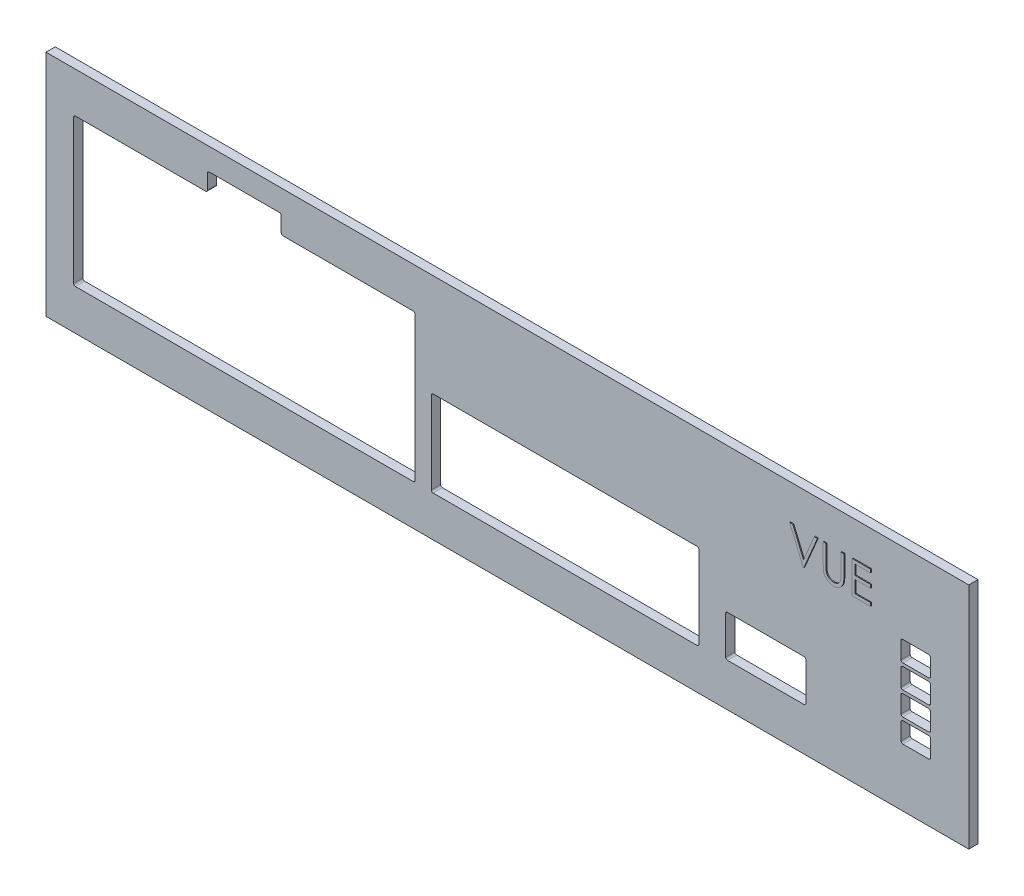
SolidWorks part; units mm, degrees
material "6061-T6 (SS)"
ref_plane "Plan de face" through (0, 0, 0) normal (0, 0, 1) x (1, 0, 0)
ref_plane "Plan de dessus" through (0, 0, 0) normal (0, 1, 0) x (1, 0, 0)
ref_plane "Plan de droite" through (0, 0, 0) normal (1, 0, 0) x (0, 0, -1)
sketch "Esquisse1" plane through (0, 0, 0) normal (0, 0, 1) x (1, 0, 0)
  line L1 (-50, 12.4) -> (50, 12.4)
  line L2 (-50, 12.4) -> (-50, -12.4)
  line L3 (-50, -12.4) -> (50, -12.4)
  line L4 (50, 12.4) -> (50, -12.4)
  point P4 (0, 12.4)
  point P7 (-50, 0)
  dimension "D1" = 100
  dimension "D2" = 24.8
extrude "Boss.-Extru.1" add sketch "Esquisse1" along normal blind 1
sketch "Esquisse2" plane through (0, 0, 1) normal (0, 0, 1) x (1, 0, 0)
  line L0 (-50, 12.4) -> (-50, -12.4) construction
  line L1 (-47.0074, 8) -> (-32.5074, 8)
  line L2 (-47.0074, 8) -> (-47.0074, -8)
  line L3 (-47.0074, -8) -> (-10.0074, -8)
  line L4 (-10.0074, 8) -> (-10.0074, -8)
  line L5 (-8.25, 1.3) -> (20.75, 1.3)
  line L6 (-8.25, 1.3) -> (-8.25, -8)
  line L7 (-8.25, -8) -> (20.75, -8)
  line L8 (20.75, 1.3) -> (20.75, -8)
  line L9 (23.65, -3.25) -> (32.35, -3.25)
  line L10 (23.65, -3.25) -> (23.65, -7.75)
  line L11 (23.65, -7.75) -> (32.35, -7.75)
  line L12 (32.35, -3.25) -> (32.35, -7.75)
  line L13 (44.256, 3.6051) -> (44.256, -6.0149) construction
  line L14 (45.756, 3.6051) -> (42.756, 3.6051) construction
  line L15 (42.756, -6.0149) -> (45.756, -6.0149) construction
  line L17 (23.65, -7.75) -> (32.35, -3.25) construction
  line L18 (42.656, 1.51) -> (45.856, 1.51)
  line L19 (22.5, -10) -> (33.5, -10) construction
  line L20 (22.5, -10) -> (22.5, -1) construction
  line L21 (22.5, -1) -> (33.5, -1) construction
  line L22 (33.5, -10) -> (33.5, -1) construction
  line L23 (22.5, -10) -> (33.5, -1) construction
  line L24 (22.5, -1) -> (33.5, -10) construction
  line L25 (42.656, 1.51) -> (42.656, 3.71)
  line L26 (42.656, 3.71) -> (45.856, 3.71)
  line L27 (45.856, 1.51) -> (45.856, 3.71)
  line L28 (42.656, 1.51) -> (45.856, 3.71) construction
  line L29 (42.656, 3.71) -> (45.856, 1.51) construction
  line L30 (42.656, -1.03) -> (45.856, -1.03)
  line L31 (42.656, -1.03) -> (42.656, 1.17)
  line L32 (-50, -12.4) -> (50, -12.4) construction
  line L33 (42.656, 1.17) -> (45.856, 1.17)
  line L34 (-24.5074, 8) -> (-10.0074, 8)
  line L35 (50, 12.4) -> (-50, 12.4) construction
  line L36 (-32.5074, 8) -> (-32.5074, 10)
  line L37 (-32.5074, 10) -> (-24.5074, 10)
  line L38 (-24.5074, 8) -> (-24.5074, 10)
  line L39 (45.856, -1.03) -> (45.856, 1.17)
  line L40 (42.656, -1.03) -> (45.856, 1.17) construction
  line L41 (42.656, 1.17) -> (45.856, -1.03) construction
  line L42 (42.656, -3.57) -> (45.856, -3.57)
  line L43 (42.656, -3.57) -> (42.656, -1.37)
  line L44 (42.656, -1.37) -> (45.856, -1.37)
  line L45 (45.856, -3.57) -> (45.856, -1.37)
  line L46 (42.656, -3.57) -> (45.856, -1.37) construction
  line L47 (42.656, -1.37) -> (45.856, -3.57) construction
  line L48 (42.656, -6.11) -> (45.856, -6.11)
  line L49 (42.656, -6.11) -> (42.656, -3.91)
  line L50 (42.656, -3.91) -> (45.856, -3.91)
  line L51 (45.856, -6.11) -> (45.856, -3.91)
  line L52 (42.656, -6.11) -> (45.856, -3.91) construction
  line L53 (42.656, -3.91) -> (45.856, -6.11) construction
  point P18 (44.256, 2.61)
  point P24 (-47.0074, 0)
  point P25 (-50, 0)
  point P26 (28, -5.5)
  point P27 (28, -5.5)
  point P33 (44.256, 0.07)
  point P38 (44.256, -2.47)
  point P43 (-28.5074, 8)
  point P48 (-28.5074, 10)
  point P49 (0, 12.4)
  point P50 (6.25, 1.3)
  point P53 (28, -3.25)
  point P56 (44.256, -5.01)
  dimension "D10" = 3.2
  dimension "D11" = 2.2
  dimension "D12" = 2.54
  dimension "D1" = 37
  dimension "D2" = 16
  dimension "D3" = 6.25
  dimension "D4" = 29
  dimension "D5" = 28
  dimension "D6" = 8.7
  dimension "D7" = 4.5
  dimension "D8" = 11
  dimension "D9" = 9
  dimension "D13" = 2.54
  dimension "D14" = 2.54
  dimension "D15" = 9.79
  dimension "D20" = 2.4
  dimension "D24" = 9.3
  dimension "D25" = 2
  dimension "D26" = 8
  dimension "D27" = 0.25
  dimension "D28" = 28.5074
extrude "Enlèv. mat.-Extru.1" cut sketch "Esquisse2" against normal through all
sketch "Esquisse3" plane through (0, 0, 1) normal (0, 0, 1) x (1, 0, 0)
  text T0 "VUE"
fillet "Congé1" radius 0.2 32 edges at (42.656, -6.11, 0.5) (42.656, -3.57, 0.5) (42.656, -1.03, 0.5) (42.656, 1.51, 0.5) (42.656, -3.91, 0.5) (42.656, -1.37, 0.5) (42.656, 1.17, 0.5) (42.656, 3.71, 0.5) (45.856, 3.71, 0.5) (45.856, 1.17, 0.5) (45.856, -1.37, 0.5) (45.856, -3.91, 0.5) (45.856, 1.51, 0.5) (45.856, -1.03, 0.5) (45.856, -3.57, 0.5) (45.856, -6.11, 0.5) (32.35, -7.75, 0.5) (23.65, -7.75, 0.5) (23.65, -3.25, 0.5) (32.35, -3.25, 0.5) (20.75, 1.3, 0.5) (20.75, -8, 0.5) (-8.25, 1.3, 0.5) (-8.25, -8, 0.5) (-47.0074, -8, 0.5) (-10.0074, -8, 0.5) (-10.0074, 8, 0.5) (-24.5074, 10, 0.5) (-24.5074, 8, 0.5) (-32.5074, 10, 0.5) (-32.5074, 8, 0.5) (-47.0074, 8, 0.5)
extrude "Boss.-Extru.2" add sketch "Esquisse3" along normal blind 0.1
